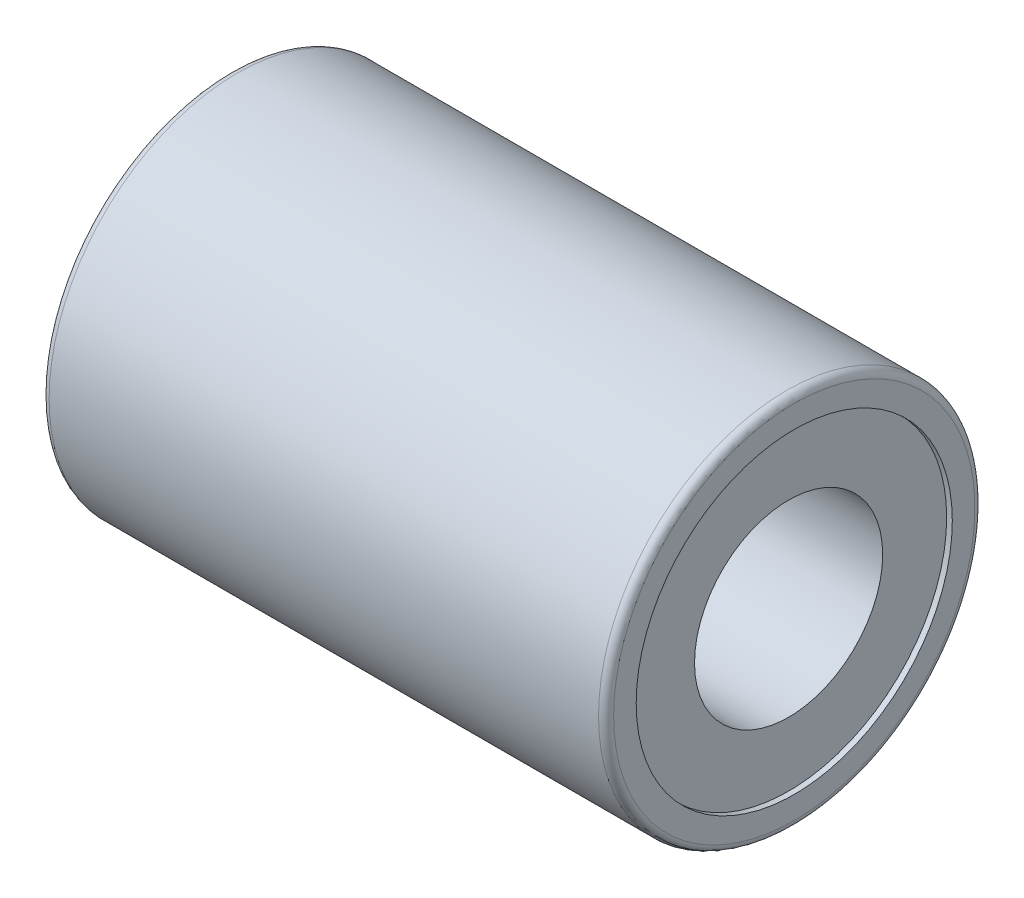
SolidWorks part; units mm, degrees
ref_plane "Front Plane" through (0, 0, 0) normal (0, 0, 1) x (1, 0, 0)
ref_plane "Top Plane" through (0, 0, 0) normal (0, 1, 0) x (1, 0, 0)
ref_plane "Right Plane" through (0, 0, 0) normal (1, 0, 0) x (0, 0, -1)
ref_plane "Plane1" through (0, 0, 0) normal (0, 0, -1) x (-1, 0, 0)
sketch "Sketch1" plane through (0, 0, 0) normal (0, 0, -1) x (-1, 0, 0)
  line L0 (5.84, 4) -> (-5.84, 4)
  line L1 (-6, 3.84) -> (-6, 3.36)
  line L2 (-6, 3.36) -> (-5.88, 3.36)
  line L3 (-5.88, 3.36) -> (-5.88, 2)
  line L4 (-5.88, 2) -> (5.88, 2)
  line L5 (5.88, 2) -> (5.88, 3.36)
  line L6 (5.88, 3.36) -> (6, 3.36)
  line L7 (6, 3.36) -> (6, 3.84)
  line L8 (-6, 0) -> (6, 0) construction
  arc A0 (-5.84, 4) -> (-6, 3.84) centre (-5.84, 3.84) ccw
  arc A1 (6, 3.84) -> (5.84, 4) centre (5.84, 3.84) ccw
revolve "Revolve1" add sketch "Sketch1" angle 360 about L8
